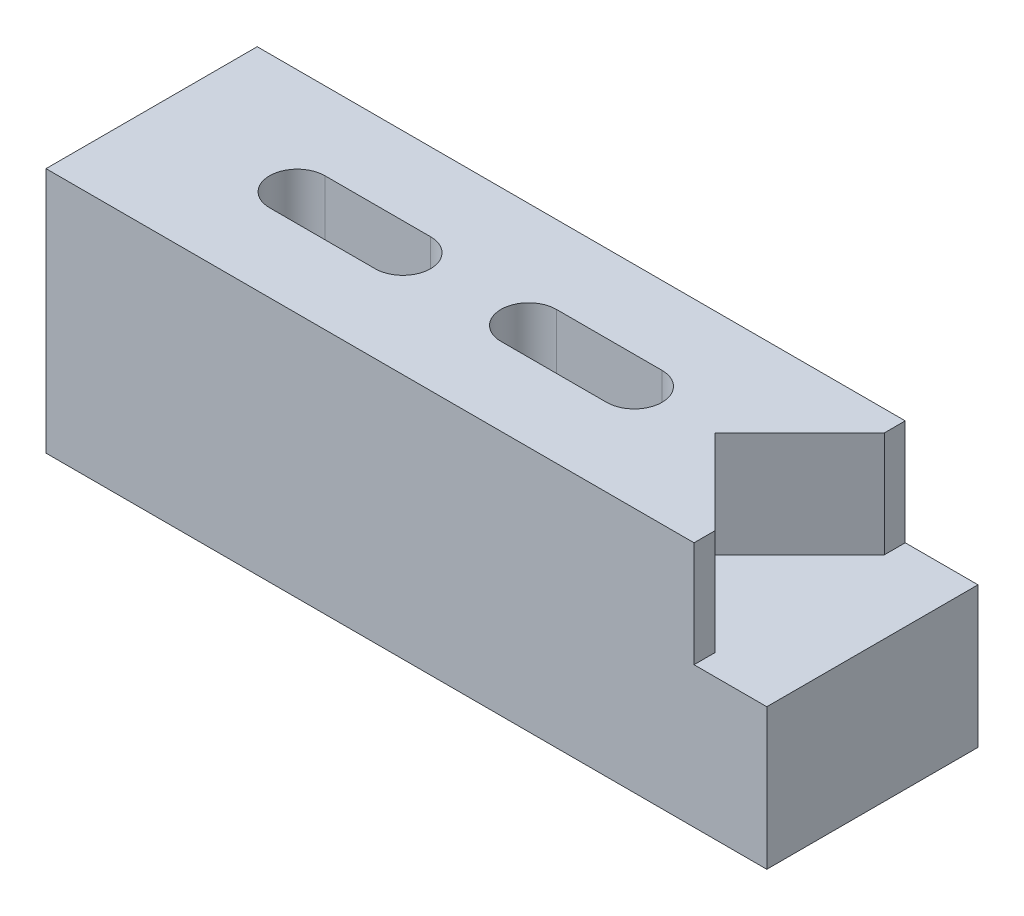
SolidWorks part; units mm, degrees
ref_plane "Front Plane" through (0, 0, 0) normal (0, 0, 1) x (1, 0, 0)
ref_plane "Top Plane" through (0, 0, 0) normal (0, 1, 0) x (1, 0, 0)
ref_plane "Right Plane" through (0, 0, 0) normal (1, 0, 0) x (0, 0, -1)
sketch "Sketch1" plane through (0, 0, 0) normal (0, 0, 1) x (1, 0, 0)
  line L0 (0, 0) -> (48.26, 0)
  line L6 (0, 0) -> (0, 17.78)
  line L10 (0, 17.78) -> (48.26, 17.78)
  line L11 (48.26, 0) -> (48.26, 17.78)
  dimension "D1" = 48.26
  dimension "D2" = 17.78
extrude "Boss-Extrude1" add sketch "Sketch1" against normal blind 15.24
sketch "Sketch3" plane through (0, 17.78, 0) normal (0, 1, 0) x (1, 0, 0)
  line L0 (48.26, 15.24) -> (40.64, 7.62)
  line L1 (40.64, 7.62) -> (48.26, 0)
  line L4 (48.26, 15.24) -> (48.26, 0)
  dimension "D2" = 90
extrude "Cut-Extrude1" cut sketch "Sketch3" against normal blind 7.62
sketch "Sketch4" plane through (0, 17.78, 0) normal (0, 1, 0) x (1, 0, 0)
  line L0 (34.83, 7.62) -> (27.21, 7.62) construction
  line L1 (34.83, 5.62) -> (27.21, 5.62)
  line L2 (34.83, 9.62) -> (27.21, 9.62)
  line L3 (18.13, 7.62) -> (10.51, 7.62) construction
  line L4 (18.13, 5.62) -> (10.51, 5.62)
  line L5 (18.13, 9.62) -> (10.51, 9.62)
  line L6 (48.26, 0) -> (0, 0) construction
  arc A0 (34.83, 5.62) -> (34.83, 9.62) centre (34.83, 7.62) ccw
  arc A1 (27.21, 9.62) -> (27.21, 5.62) centre (27.21, 7.62) ccw
  arc A2 (18.13, 5.62) -> (18.13, 9.62) centre (18.13, 7.62) ccw
  arc A3 (10.51, 9.62) -> (10.51, 5.62) centre (10.51, 7.62) ccw
  point P2 (31.02, 7.62)
  point P7 (14.32, 7.62)
  point P14 (36.83, 7.62)
  point P16 (8.51, 7.62)
  point P18 (20.13, 7.62)
  point P19 (25.21, 7.62)
  dimension "D1" = 4
  dimension "D2" = 3.81
  dimension "D3" = 7.62
  dimension "D4" = 7.62
  dimension "D5" = 5.08
extrude "Cut-Extrude2" cut sketch "Sketch4" against normal through all
sketch "Sketch5" plane through (48.26, 0, 0) normal (1, 0, 0) x (0, 0, -1)
  line L1 (0, 10.16) -> (15.24, 10.16)
  line L2 (0, 10.16) -> (0, 0)
  line L3 (0, 0) -> (15.24, 0)
  line L4 (15.24, 10.16) -> (15.24, 0)
extrude "Boss-Extrude2" add sketch "Sketch5" along normal blind 3.75
sketch "Sketch6" plane through (0, 17.78, 0) normal (0, 1, 0) x (1, 0, 0)
  line L0 (48.26, 0) -> (46.76, 0)
  line L1 (48.26, 0) -> (0, 0) construction
  line L2 (46.76, 0) -> (46.76, 1.5)
  line L3 (40.64, 7.62) -> (48.26, 0) construction
  line L4 (46.76, 1.5) -> (48.26, 0)
  dimension "D1" = 1.5
extrude "Cut-Extrude5" cut sketch "Sketch6" against normal up to surface (7.62 mm away) contours L2 L4 L0 up to face at (48.236, 10.16, -7.62)
sketch "Sketch7" plane through (0, 17.78, 0) normal (0, 1, 0) x (1, 0, 0)
  line L0 (48.26, 15.24) -> (46.76, 15.24)
  line L1 (48.26, 15.24) -> (0, 15.24) construction
  line L2 (46.76, 15.24) -> (46.76, 13.74)
  line L3 (48.26, 15.24) -> (40.64, 7.62) construction
  line L4 (46.76, 13.74) -> (48.26, 15.24)
  dimension "D1" = 1.5
extrude "Cut-Extrude7" cut sketch "Sketch7" against normal up to surface (7.62 mm away) contours L2 L4 L0 up to face at (47.74, 10.16, -6.6)
